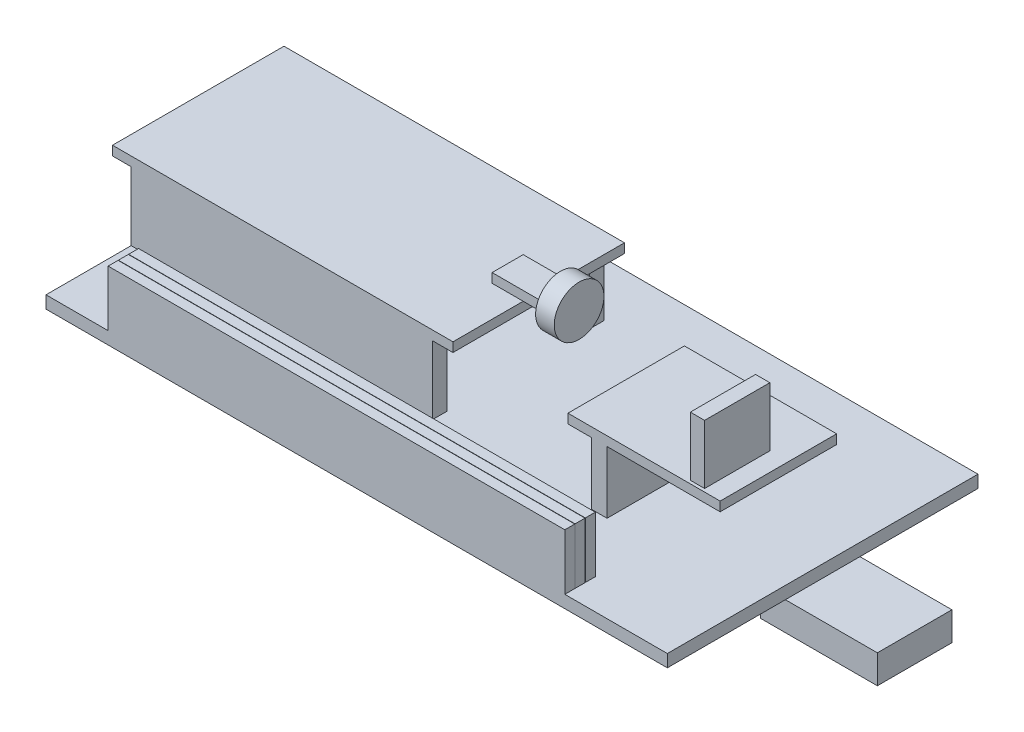
SolidWorks part; units mm, degrees
ref_plane "Front Plane" through (0, 0, 0) normal (0, 0, 1) x (1, 0, 0)
ref_plane "Top Plane" through (0, 0, 0) normal (0, 1, 0) x (1, 0, 0)
ref_plane "Right Plane" through (0, 0, 0) normal (1, 0, 0) x (0, 0, -1)
sketch "Sketch1" plane through (0, 0, 0) normal (0, 1, 0) x (1, 0, 0)
  line L1 (-50, -25) -> (50, -25)
  line L2 (-50, -25) -> (-50, 25)
  line L3 (-50, 25) -> (50, 25)
  line L4 (50, -25) -> (50, 25)
  line L5 (-50, -25) -> (50, 25) construction
  line L6 (-50, 25) -> (50, -25) construction
  point P0 (0, 0)
  dimension "D1" = 100
  dimension "D2" = 50
extrude "Boss-Extrude1" add sketch "Sketch1" along normal blind 2
sketch "Sketch2" plane through (0, 2, 0) normal (0, 1, 0) x (1, 0, 0)
  line L0 (-50, -25) -> (50, -25) construction
  line L1 (-40, -25) -> (33.5, -25)
  line L2 (-40, -25) -> (-40, -23.4)
  line L3 (-40, -23.4) -> (33.5, -23.4)
  line L4 (33.5, -25) -> (33.5, -23.4)
  line L5 (-50, 25) -> (-50, -25) construction
  point P6 (-40, -24.2)
  dimension "D1" = 10
  dimension "D2" = 73.5
  dimension "D3" = 1.6
extrude "Boss-Extrude2" add sketch "Sketch2" along normal blind 9
pattern_linear "LPattern2" count 3 spacing 1.65 along (0, 0, -1) of "Boss-Extrude2"
sketch "Sketch3" plane through (0, 0, 0) normal (0, -1, 0) x (1, 0, 0)
  line L1 (46, -6) -> (64.8, -6)
  line L2 (46, -6) -> (46, 6)
  line L3 (46, 6) -> (64.8, 6)
  line L4 (64.8, -6) -> (64.8, 6)
  line L5 (6.05, 0) -> (-6.05, 0) construction
  line L6 (50, 25) -> (50, -25) construction
  point P4 (46, 0)
  dimension "D1" = 12
  dimension "D2" = 4
  dimension "D3" = 18.8
extrude "Boss-Extrude3" add sketch "Sketch3" along normal blind 4.6
sketch "Sketch4" plane through (0, 2, 0) normal (0, 1, 0) x (1, 0, 0)
  line L0 (-50, 25) -> (-50, -25) construction
  line L1 (-50, -11.3) -> (-1.5, -11.3)
  line L2 (-50, -11.3) -> (-50, -9)
  line L3 (-50, -9) -> (-1.5, -9)
  line L4 (-1.5, -11.3) -> (-1.5, -9)
  line L5 (-50, -25) -> (-40, -25) construction
  line L6 (-50, 14) -> (-1.5, 14)
  line L7 (-50, 14) -> (-50, 16.3)
  line L8 (-50, 16.3) -> (-1.5, 16.3)
  line L9 (-1.5, 14) -> (-1.5, 16.3)
  dimension "D1" = 13.7
  dimension "D2" = 2.3
  dimension "D3" = 48.5
  dimension "D4" = 2.3
  dimension "D5" = 23
  dimension "D6" = 48.5
extrude "Boss-Extrude4" add sketch "Sketch4" along normal blind 11
sketch "Sketch5" plane through (0, 13, 0) normal (0, 1, 0) x (1, 0, 0)
  line L0 (-1.5, 16.3) -> (-50, 16.3) construction
  line L1 (-53, 16.3) -> (1.8, 16.3)
  line L2 (-53, 16.3) -> (-53, -11.3)
  line L3 (-53, -11.3) -> (1.8, -11.3)
  line L4 (1.8, 16.3) -> (1.8, -11.3)
  line L5 (-50, -11.3) -> (-1.5, -11.3) construction
  line L6 (-50, -11.3) -> (-50, -25) construction
  dimension "D1" = 54.8
  dimension "D2" = 3
extrude "Boss-Extrude5" add sketch "Sketch5" along normal blind 1.5
sketch "Sketch6" plane through (0, 14.5, 0) normal (0, 1, 0) x (1, 0, 0)
  line L0 (1.8, -11.3) -> (1.8, 16.3) construction
  line L1 (-3.2, 5) -> (5.3, 5)
  line L2 (-3.2, 5) -> (-3.2, 0)
  line L3 (-3.2, 0) -> (5.3, 0)
  line L4 (5.3, 5) -> (5.3, 0)
  line L7 (-10.505, 0) -> (10.505, 0) construction
  point P0 (1.8, 2.5)
  dimension "D1" = 8.5
  dimension "D2" = 5
extrude "Boss-Extrude6" add sketch "Sketch6" along normal blind 1.5
sketch "Sketch7" plane through (5.3, 0, 0) normal (1, 0, 0) x (0, 0, -1)
  circle A0 centre (2.5, 15.1794) radius 4
  dimension "D1" = 8
extrude "Boss-Extrude7" add sketch "Sketch7" along normal blind 3
sketch "Sketch8" plane through (0, 2, 0) normal (0, 1, 0) x (1, 0, 0)
  line L0 (50, -25) -> (50, 25) construction
  line L1 (23.8, -0.5) -> (26.3, -0.5)
  line L2 (23.8, -0.5) -> (23.8, -11)
  line L3 (23.8, -11) -> (26.3, -11)
  line L4 (26.3, -0.5) -> (26.3, -11)
  line L5 (20, 7.75) -> (22.5, 7.75)
  line L6 (20, 7.75) -> (20, 2.5)
  line L7 (20, 2.5) -> (22.5, 2.5)
  line L8 (22.5, 7.75) -> (22.5, 2.5)
  line L9 (50, 25) -> (-50, 25) construction
  point P10 (25.05, -11)
  dimension "D1" = 26.2
  dimension "D2" = 2.5
  dimension "D3" = 10.5
  dimension "D4" = 36
  dimension "D5" = 5.25
  dimension "D6" = 2.5
  dimension "D7" = 30
  dimension "D8" = 22.5
extrude "Boss-Extrude8" add sketch "Sketch8" along normal blind 10
sketch "Sketch9" plane through (0, 12, 0) normal (0, 1, 0) x (1, 0, 0)
  line L0 (22.5, 7.75) -> (20, 7.75) construction
  line L1 (20, -11) -> (44.5, -11)
  line L2 (20, -11) -> (20, 7.75)
  line L3 (20, 7.75) -> (44.5, 7.75)
  line L4 (44.5, -11) -> (44.5, 7.75)
  line L5 (23.8, -11) -> (26.3, -11) construction
  line L6 (20, 7.75) -> (20, 2.5) construction
  dimension "D1" = 24.5
extrude "Boss-Extrude9" add sketch "Sketch9" along normal blind 1.5
sketch "Sketch10" plane through (0, 13.5, 0) normal (0, 1, 0) x (1, 0, 0)
  line L0 (-13.0787, 0) -> (13.0787, 0) construction
  line L1 (39.2, 0) -> (41.5, 0)
  line L2 (39.2, 0) -> (39.2, -10.5)
  line L3 (39.2, -10.5) -> (41.5, -10.5)
  line L4 (41.5, 0) -> (41.5, -10.5)
  line L5 (44.5, -11) -> (44.5, 7.75) construction
  dimension "D1" = 2.3
  dimension "D2" = 10.5
  dimension "D3" = 3
extrude "Boss-Extrude10" add sketch "Sketch10" along normal blind 9.5
